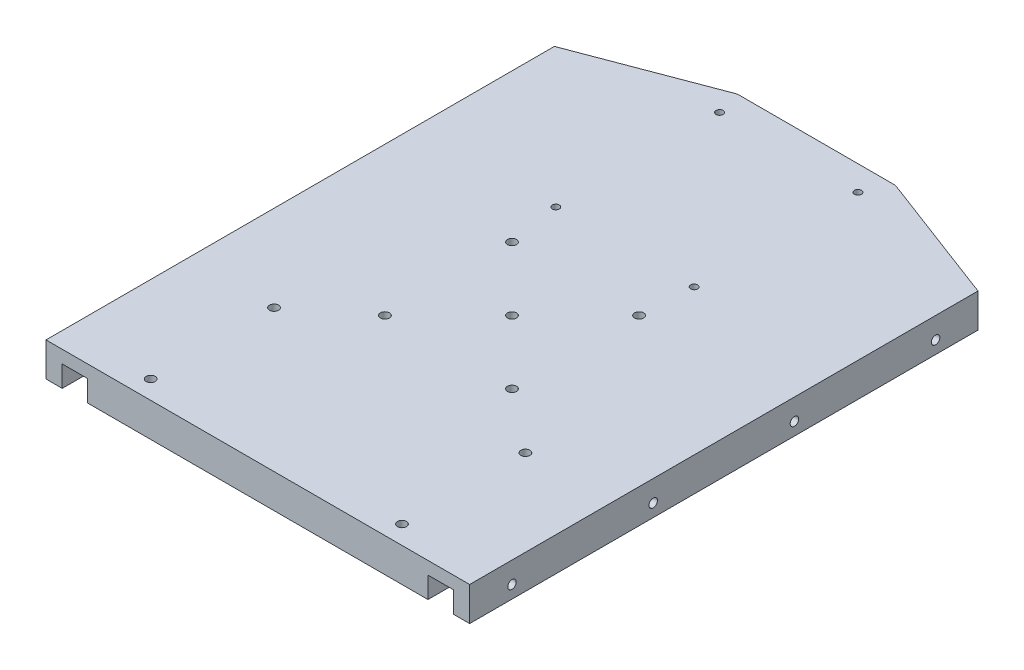
SolidWorks part; units mm, degrees
material "ABS"
ref_plane "Front Plane" through (0, 0, 0) normal (0, 0, 1) x (1, 0, 0)
ref_plane "Top Plane" through (0, 0, 0) normal (0, 1, 0) x (1, 0, 0)
ref_plane "Right Plane" through (0, 0, 0) normal (1, 0, 0) x (0, 0, -1)
sketch "Sketch1" plane through (0, 0, 0) normal (0, 1, 0) x (1, 0, 0)
  line L1 (75, 90) -> (-75, 90)
  line L2 (75, 90) -> (75, -90)
  line L3 (75, -90) -> (-75, -90)
  line L4 (-75, 90) -> (-75, -90)
  line L5 (75, 90) -> (-75, -90) construction
  line L6 (75, -90) -> (-75, 90) construction
  point P0 (0, 0)
  dimension "D1" = 150
  dimension "D2" = 180
extrude "Boss-Extrude1" add sketch "Sketch1" along normal blind 12
sketch "Sketch2" plane through (75, 0, 0) normal (1, 0, 0) x (0, 0, -1)
  line L0 (-90, 6) -> (90, 6) construction
  line L1 (-90, 12) -> (-90, 0) construction
  line L2 (90, 12) -> (90, 0) construction
hole_wizard "Ø3.0mm Dowel Hole1" positions "Sketch5" profile "Sketch6" hole size "Ø3.0" standard "ISO"
sketch "Sketch5" plane through (75, 0, 0) normal (1, 0, 0) x (0, 0, -1)
  line L1 (0, 55) -> (0, -55) construction
  line L2 (-90, 0) -> (90, 0) construction
  point P0 (-25, 4.5)
  point P12 (-75, 4.5)
  point P16 (75, 4.5)
  point P18 (25, 4.5)
  point P21 (-50, 4.5) [skipped]
  dimension "D1" = 25
  dimension "D3" = 4.5
  dimension "D4" = 50
  dimension "D2" = 3
sketch "Sketch6" plane through (75, 4.5, 25) normal (0, 1, 0) x (0, 0, -1)
  line L0 (0, 0) -> (0, 5.9013)
  line L1 (0, 5.9013) -> (1.5, 5)
  line L2 (1.5, 5) -> (1.5, 0)
  line L5 (1.5, 0) -> (0, 0)
  line L10 (0, 5.9013) -> (-1.5, 5) construction
  line L11 (0, -6.35) -> (0, 107.95) construction
  dimension "Hole Dia." = 3
  dimension "Hole Depth" = 5
  dimension "Drill Angle" = 118
mirror "Mirror1" about plane through (0, 0, 0) normal (1, 0, 0) of "Ø3.0mm Dowel Hole1"
sketch "Sketch7" plane through (0, 12, 0) normal (0, 1, 0) x (1, 0, 0)
  line L1 (70, 15) -> (-70, 15) construction
  line L2 (70, 15) -> (70, -15) construction
  line L3 (70, -15) -> (-70, -15) construction
  line L4 (-70, 15) -> (-70, -15) construction
  line L5 (70, 15) -> (-70, -15) construction
  line L6 (70, -15) -> (-70, 15) construction
  point P0 (0, 0)
  dimension "D1" = 30
  dimension "D2" = 140
sketch "Sketch10" plane through (0, 12, 0) normal (0, 1, 0) x (1, 0, 0)
  line L1 (-68, 68) -> (68, 68) construction
  line L2 (-68, 68) -> (-68, -68) construction
  line L3 (-68, -68) -> (68, -68) construction
  line L4 (68, 68) -> (68, -68) construction
  line L5 (-68, 68) -> (68, -68) construction
  line L6 (-68, -68) -> (68, 68) construction
  point P0 (0, 0)
  dimension "D1" = 136
sketch "Sketch13" plane through (0, 12, 0) normal (0, 1, 0) x (1, 0, 0)
  line L16 (-75, -90) -> (75, -90) construction
  line L21 (-6.6, 0) -> (6.6, 0) construction
  line L22 (-24.5, 89) -> (24.5, 31) construction
  line L23 (-24.5, 31) -> (24.5, 89) construction
  line L24 (24.5, 31) -> (24.5, 89) construction
  line L25 (-24.5, 89) -> (24.5, 89) construction
  line L26 (-24.5, 31) -> (-24.5, 89) construction
  line L27 (-24.5, 31) -> (24.5, 31) construction
  line L28 (-28, 107.78) -> (28, 22.78) construction
  line L29 (-28, 22.78) -> (28, 107.78) construction
  line L30 (28, 22.78) -> (28, 107.78) construction
  line L31 (-28, 107.78) -> (28, 107.78) construction
  line L32 (-28, 22.78) -> (-28, 107.78) construction
  line L33 (-28, 22.78) -> (28, 22.78) construction
  line L34 (-75, 90) -> (75, 90)
  line L35 (28, 107.78) -> (75, 90)
  line L36 (-28, 107.78) -> (28, 107.78)
  line L37 (-75, 90) -> (-28, 107.78)
  point P27 (0, 60)
  point P28 (0, 65.28)
  dimension "D1" = 56
  dimension "D2" = 85
  dimension "D3" = 49
  dimension "D4" = 58
  dimension "D5" = 5.28
  dimension "D6" = 60
extrude "Boss-Extrude2" add sketch "Sketch13" against normal up to surface (12 mm away) up to face at (0, 0, 0)
fillet "Fillet4" radius 3 2 edges at (-28, 6, -107.78) (28, 6, -107.78)
sketch "Sketch14" plane through (0, 12, 0) normal (0, 1, 0) x (1, 0, 0)
  line L0 (-30, 107.78) -> (30, 107.78)
  line L5 (-30, 107.78) -> (-30, 22.78)
  line L7 (30, 107.78) -> (30, 22.78)
  line L8 (27.4515, 107.78) -> (-27.4515, 107.78) construction
  line L18 (-30, 22.78) -> (30, 22.78)
  point P7 (0, 107.78)
  dimension "D1" = 85
  dimension "D2" = 60
extrude "Cut-Extrude1" cut sketch "Sketch14" along normal blind 7 from surface at -12 starting at face at (0, 0, -53.8535)
sketch "Sketch17" plane through (0, 7, 0) normal (0, -1, 0) x (-1, 0, 0)
  line L10 (30, 22.78) -> (30, 107.0234) construction
  line L11 (-30, 22.78) -> (30, 22.78) construction
  line L22 (-23.5, 99) -> (25.5, 41) construction
  line L23 (-23.5, 41) -> (25.5, 99) construction
  line L24 (25.5, 41) -> (25.5, 99) construction
  line L25 (-23.5, 99) -> (25.5, 99) construction
  line L26 (-23.5, 41) -> (-23.5, 99) construction
  line L27 (-23.5, 41) -> (25.5, 41) construction
  line L28 (-28, 117.78) -> (30, 32.78) construction
  line L29 (-28, 32.78) -> (30, 117.78) construction
  line L30 (30, 32.78) -> (30, 117.78) construction
  line L31 (-28, 117.78) -> (30, 117.78) construction
  line L32 (-28, 32.78) -> (-28, 117.78) construction
  line L33 (-28, 32.78) -> (30, 32.78) construction
  line L36 (-28, 117.78) -> (30, 117.78)
  circle A0 centre (25.5, 99) radius 1.25
  circle A1 centre (-23.5, 99) radius 1.25
  circle A2 centre (25.5, 41) radius 1.25
  circle A3 centre (-23.5, 41) radius 1.25
  point P27 (1, 70)
  point P28 (1, 75.28)
  dimension "D6" = 2.5
  dimension "D1" = 58
  dimension "D2" = 85
  dimension "D3" = 49
  dimension "D4" = 58
  dimension "D5" = 5.28
  dimension "D7" = 10
extrude "Cut-Extrude2" cut sketch "Sketch17" against normal through all contours A1 | A0 | A2 | A3
sketch "Sketch18" plane through (0, 0, 0) normal (0, -1, 0) x (1, 0, 0)
  line L0 (-75, 90) -> (75, 90) construction
  line L1 (69.25, 90) -> (60.25, 90)
  line L2 (69.25, 90) -> (69.25, -95.5799)
  line L3 (69.25, -95.5799) -> (60.25, -95.5799)
  line L4 (60.25, 90) -> (60.25, -95.5799)
  line L5 (75, -90) -> (30, -107.0234) construction
  line L6 (75, 90) -> (75, -90) construction
  line L7 (0, -6.6) -> (0, 6.6) construction
  line L8 (-69.25, -95.5799) -> (-60.25, -95.5799)
  line L9 (-60.25, 90) -> (-60.25, -95.5799)
  line L10 (-69.25, 90) -> (-60.25, 90)
  line L11 (-69.25, 90) -> (-69.25, -95.5799)
  dimension "D1" = 5.75
  dimension "D2" = 9
extrude "Cut-Extrude3" cut sketch "Sketch18" against normal blind 7.5
hole_wizard "M3 Clearance Hole1" positions "Sketch19" profile "Sketch20" hole size "M3" standard "ISO" end condition through all
sketch "Sketch19" plane through (0, 12, 0) normal (0, 1, 0) x (1, 0, 0)
  line L1 (-75, -90) -> (-44.5, -90) construction
  line L2 (-75, -90) -> (-75, -83.45) construction
  line L3 (-75, -83.45) -> (-44.5, -83.45) construction
  line L4 (-44.5, -90) -> (-44.5, -83.45) construction
  point P0 (-44.5, -83.45)
  point P2 (-44.5, -39.75)
  point P66 (-44.5, -83.45)
  point P67 (0, 0)
  dimension "D1" = 30.5
  dimension "D2" = 6.55
  dimension "D3" = 43.7
sketch "Sketch20" plane through (-44.5, 12, 83.45) normal (1, 0, 0) x (0, 0, 1)
  line L0 (0, 0) -> (0, 12)
  line L1 (0, 12) -> (1.6, 12)
  line L2 (1.6, 12) -> (1.6, 0)
  line L5 (1.6, 0) -> (0, 0)
  line L11 (0, -6.35) -> (0, 107.95) construction
  dimension "Thru Hole Dia." = 3.2
  dimension "Thru Hole Depth" = 12
mirror "Mirror2" about plane through (0, 0, 0) normal (1, 0, 0) of "M3 Clearance Hole1"
hole_wizard "M3 Clearance Hole2" positions "Sketch21" profile "Sketch22" hole size "M3" standard "ISO" end condition through all
sketch "Sketch21" plane through (0, 12, 0) normal (0, 1, 0) x (1, 0, 0)
  line L1 (22.5, 22.5) -> (-22.5, 22.5) construction
  line L2 (22.5, 22.5) -> (22.5, -22.5) construction
  line L3 (22.5, -22.5) -> (-22.5, -22.5) construction
  line L4 (-22.5, 22.5) -> (-22.5, -22.5) construction
  line L5 (22.5, 22.5) -> (-22.5, -22.5) construction
  line L6 (22.5, -22.5) -> (-22.5, 22.5) construction
  line L7 (-68, -68) -> (68, 68) construction
  point P0 (0, 0)
  point P1 (-22.5, -22.5)
  point P60 (22.5, 22.5)
  point P61 (22.5, -22.5)
  point P62 (-22.5, 22.5)
  dimension "D1" = 45
sketch "Sketch22" plane through (0, 12, 0) normal (1, 0, 0) x (0, 0, 1)
  line L0 (0, 0) -> (0, 12)
  line L1 (0, 12) -> (1.6, 12)
  line L2 (1.6, 12) -> (1.6, 0)
  line L5 (1.6, 0) -> (0, 0)
  line L11 (0, -6.35) -> (0, 107.95) construction
  dimension "Thru Hole Dia." = 3.2
  dimension "Thru Hole Depth" = 12
